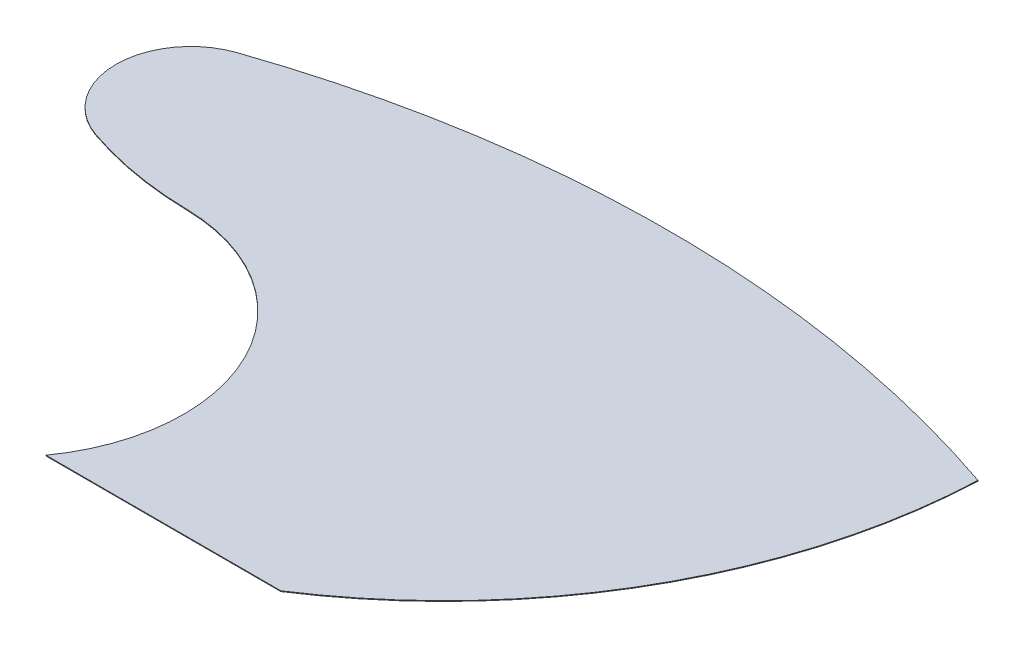
SolidWorks part; units mm, degrees
ref_plane "Front Plane" through (0, 0, 0) normal (0, 0, 1) x (1, 0, 0)
ref_plane "Top Plane" through (0, 0, 0) normal (0, 1, 0) x (1, 0, 0)
ref_plane "Right Plane" through (0, 0, 0) normal (1, 0, 0) x (0, 0, -1)
sketch "Sketch2"
sketch "Sketch1" plane through (0, 0, 0) normal (0, 1, 0) x (1, 0, 0)
  line L2 (-44.0532, 146.9643) -> (109.5118, 146.9643) construction
  line L3 (77.0118, 6.9643) -> (142.0118, 6.9643)
  line L6 (-6.9882, 171.2184) -> (-6.9882, 110.3316) construction
  line L8 (78.6218, 145.4671) -> (82.6066, 100.6438) construction
  line L9 (58.7004, 143.696) -> (98.5432, 147.2381) construction
  line L10 (68.6611, 144.5815) -> (80.8356, 120.5653) construction
  line L11 (80.8356, 120.5653) -> (88.5825, 146.3526) construction
  line L12 (58.7004, 143.696) -> (82.6066, 100.6438) construction
  line L13 (82.6066, 100.6438) -> (98.5432, 147.2381) construction
  arc A14 (7.0118, 129.9173) -> (212.0118, 129.9173) centre (109.5118, -169.7148) cw
  arc A17 (142.0118, 6.9643) -> (212.0118, 129.9173) centre (57.9998, 136.1971) ccw
  arc A20 (77.0118, 6.9643) -> (37.5542, 85.3939) centre (36.695, 35.8214) ccw
  arc A22 (7.0118, 129.9173) -> (7.0118, 90.7459) centre (13.7118, 110.3316) ccw
  arc A23 (37.5542, 85.3939) -> (7.0118, 90.7459) centre (39.2819, 185.079) cw
  point P6 (109.5118, 6.9643)
  point P19 (80.8356, 120.5653)
  point P20 (68.6611, 144.5815)
  point P21 (109.5118, 146.9643)
  point P23 (88.5825, 146.3526)
  dimension "D1" = 20.7
  dimension "D2" = 154.14
  dimension "D3" = 219
  dimension "D6" = 49.58
  dimension "D8" = 70
  dimension "D7" = 99.7
  dimension "D4" = 140
  dimension "D5" = 65
  dimension "D9" = 85.61
  dimension "D10" = 40
  dimension "D11" = 45
  dimension "D12" = 25
  dimension "D13" = 10
  dimension "D14" = 10
extrude "Boss-Extrude1" add sketch "Sketch1" along normal blind 0.2
